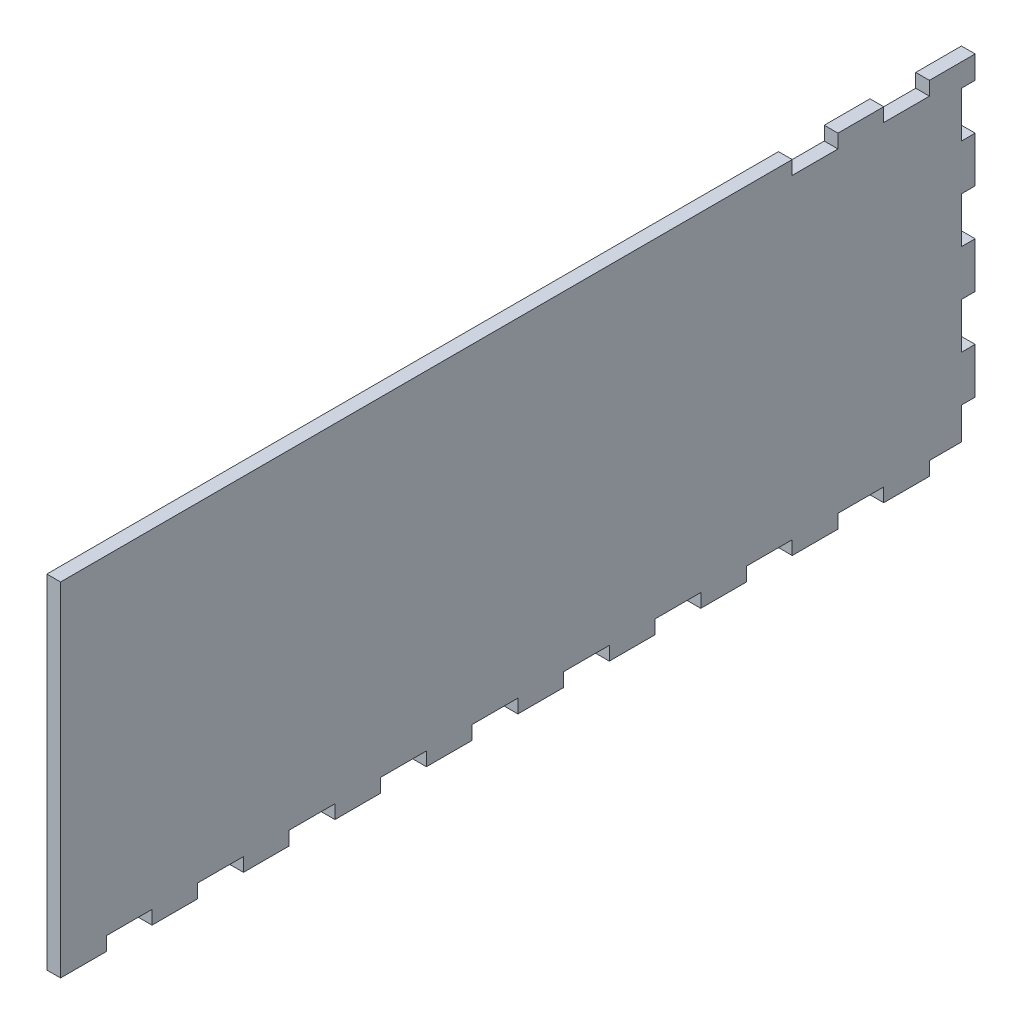
SolidWorks part; units mm, degrees
ref_plane "Plano frontal" through (0, 0, 0) normal (0, 0, 1) x (1, 0, 0)
ref_plane "Plano superior" through (0, 0, 0) normal (0, 1, 0) x (1, 0, 0)
ref_plane "Plano direito" through (0, 0, 0) normal (1, 0, 0) x (0, 0, -1)
sketch "mdfEsb" plane through (0, 0, 0) normal (1, 0, 0) x (0, 0, -1)
  line L1 (0, 0) -> (200, 0)
  line L2 (0, 0) -> (0, 75)
  line L3 (0, 75) -> (200, 75)
  line L4 (200, 0) -> (200, 75)
  dimension "D1" = 200
  dimension "D2" = 75
extrude "mdf" add sketch "mdfEsb" along normal blind 3
sketch "entradasEsb" plane through (3, 0, 0) normal (1, 0, 0) x (0, 0, -1)
  line L0 (0, 0) -> (200, 0) construction
  line L1 (10, 0) -> (20, 0)
  line L2 (10, 0) -> (10, 3)
  line L3 (10, 3) -> (20, 3)
  line L4 (20, 0) -> (20, 3)
  line L5 (30, 0) -> (30, 3)
  line L6 (30, 0) -> (40, 0)
  line L7 (40, 0) -> (40, 3)
  line L8 (30, 3) -> (40, 3)
  line L9 (50, 0) -> (50, 3)
  line L10 (50, 0) -> (60, 0)
  line L11 (60, 0) -> (60, 3)
  line L12 (50, 3) -> (60, 3)
  line L13 (70, 0) -> (70, 3)
  line L14 (70, 0) -> (80, 0)
  line L15 (80, 0) -> (80, 3)
  line L16 (70, 3) -> (80, 3)
  line L17 (90, 0) -> (90, 3)
  line L18 (90, 0) -> (100, 0)
  line L19 (100, 0) -> (100, 3)
  line L20 (90, 3) -> (100, 3)
  line L21 (110, 0) -> (110, 3)
  line L22 (110, 0) -> (120, 0)
  line L23 (120, 0) -> (120, 3)
  line L24 (110, 3) -> (120, 3)
  line L25 (130, 0) -> (130, 3)
  line L26 (130, 0) -> (140, 0)
  line L27 (140, 0) -> (140, 3)
  line L28 (130, 3) -> (140, 3)
  line L29 (150, 0) -> (150, 3)
  line L30 (150, 0) -> (160, 0)
  line L31 (160, 0) -> (160, 3)
  line L32 (150, 3) -> (160, 3)
  line L33 (170, 0) -> (170, 3)
  line L34 (170, 0) -> (180, 0)
  line L35 (180, 0) -> (180, 3)
  line L36 (170, 3) -> (180, 3)
  line L41 (10, 0) -> (30, 0) construction
  line L42 (200, 0) -> (200, 75) construction
  line L43 (200, 20) -> (197, 20)
  line L44 (200, 20) -> (200, 30)
  line L45 (200, 30) -> (197, 30)
  line L46 (197, 20) -> (197, 30)
  line L47 (200, 40) -> (200, 50)
  line L48 (200, 40) -> (197, 40)
  line L49 (197, 40) -> (197, 50)
  line L50 (200, 50) -> (197, 50)
  line L51 (200, 60) -> (200, 70)
  line L52 (200, 60) -> (197, 60)
  line L53 (197, 60) -> (197, 70)
  line L54 (200, 70) -> (197, 70)
  line L55 (200, 20) -> (200, 40) construction
  line L56 (190, 0) -> (190, 3)
  line L57 (190, 3) -> (197, 3)
  line L58 (197, 3) -> (197, 10)
  line L59 (197, 10) -> (200, 10)
  line L60 (200, 10) -> (200, 0)
  line L61 (200, 0) -> (190, 0)
  line L62 (200, 75) -> (0, 75) construction
  line L63 (190, 75) -> (180, 75)
  line L64 (190, 75) -> (190, 72)
  line L65 (190, 72) -> (180, 72)
  line L66 (180, 75) -> (180, 72)
  line L67 (170, 75) -> (170, 72)
  line L68 (170, 75) -> (160, 75)
  line L69 (160, 75) -> (160, 72)
  line L70 (170, 72) -> (160, 72)
  line L71 (190, 75) -> (170, 75) construction
  point P70 (190, 73.5)
  dimension "D1" = 3
  dimension "D2" = 10
  dimension "D3" = 10
  dimension "D5" = 20
  dimension "D6" = 3
  dimension "D7" = 20
  dimension "D8" = 10
  dimension "D10" = 20
  dimension "D11" = 10
  dimension "D12" = 10
  dimension "D13" = 3
  dimension "D14" = 3
  dimension "D15" = 10
  dimension "D16" = 10
  dimension "D17" = 3
  dimension "D19" = 20
  dimension "D4" = 9
  dimension "D9" = 3
  dimension "D18" = 2
extrude "Entradas" cut sketch "entradasEsb" against normal blind 3
